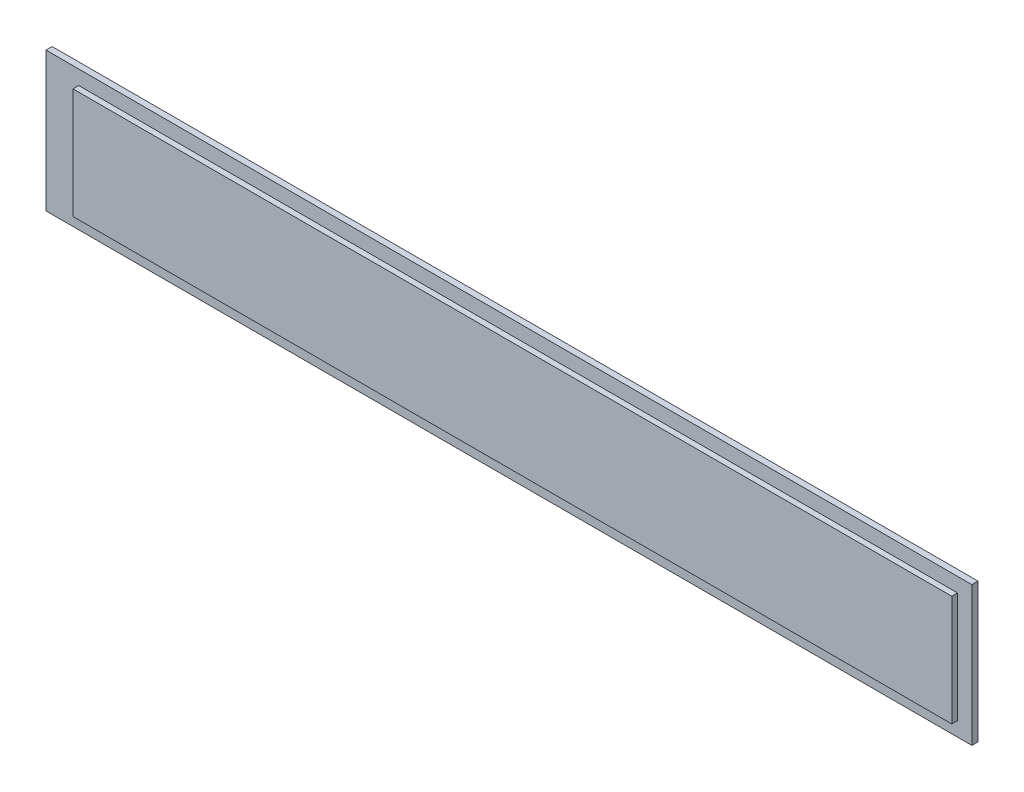
SolidWorks part; units mm, degrees
ref_plane "Спереди" through (0, 0, 0) normal (0, 0, 1) x (1, 0, 0)
ref_plane "Сверху" through (0, 0, 0) normal (0, 1, 0) x (1, 0, 0)
ref_plane "Справа" through (0, 0, 0) normal (1, 0, 0) x (0, 0, -1)
other "Configuration Table"
sketch "Эскиз1" plane through (0, 0, 0) normal (0, 0, 1) x (1, 0, 0)
  line L0 (-5, 21.1) -> (221, 21.1)
  line L1 (221, 21.1) -> (221, -12.9)
  line L2 (221, -12.9) -> (-5, -12.9)
  line L3 (-5, -12.9) -> (-5, 21.1)
  line L4 (3, 17.6) -> (217.5, 17.6)
  line L5 (217.5, 17.6) -> (217.5, -9.4)
  line L6 (217.5, -9.4) -> (3, -9.4)
  line L7 (3, -9.4) -> (3, 17.6)
extrude "Бобышка-Вытянуть1" add sketch "Эскиз1" along normal blind 0.1 contours L7 L4 L5 L6 | L3 L0 L1 L2
sketch "Эскиз2" plane through (0, 0, 0) normal (0, 0, -1) x (-1, 0, 0)
  line L0 (-221, 21.1) -> (5, 21.1)
  line L1 (5, 21.1) -> (5, -12.9)
  line L2 (5, -12.9) -> (-221, -12.9)
  line L3 (-221, -12.9) -> (-221, 21.1)
extrude "Бобышка-Вытянуть2" add sketch "Эскиз2" along normal blind 1.4
sketch "Эскиз3" plane through (0, 0, 0) normal (0, 0, 1) x (1, 0, 0)
  line L0 (3, 17.6) -> (217.5, 17.6)
  line L1 (217.5, 17.6) -> (217.5, -9.4)
  line L2 (217.5, -9.4) -> (3, -9.4)
  line L3 (3, -9.4) -> (3, 17.6)
extrude "Бобышка-Вытянуть3" add sketch "Эскиз3" along normal blind 1.5
